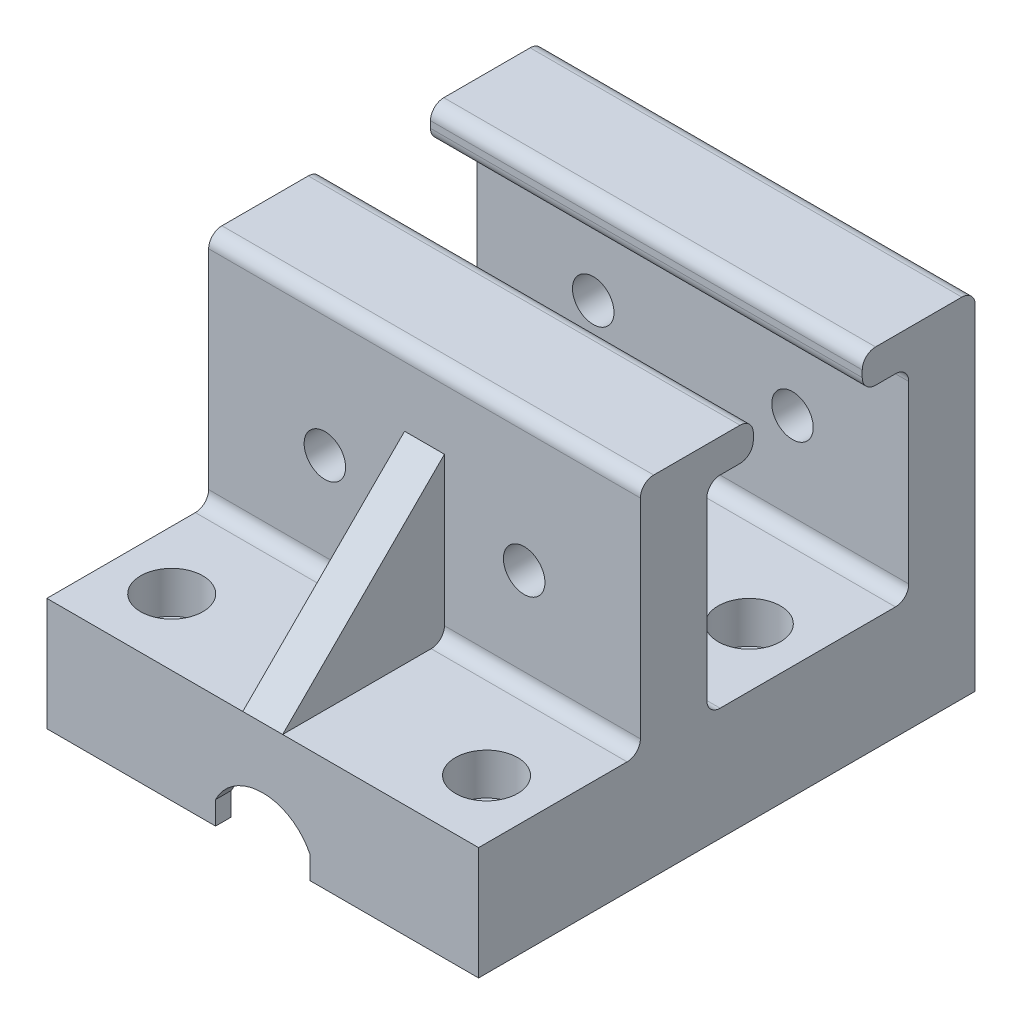
SolidWorks part; units mm, degrees
ref_plane "Front Plane" through (0, 0, 0) normal (0, 0, 1) x (1, 0, 0)
ref_plane "Top Plane" through (0, 0, 0) normal (0, 1, 0) x (1, 0, 0)
ref_plane "Right Plane" through (0, 0, 0) normal (1, 0, 0) x (0, 0, -1)
sketch "Sketch1" plane through (0, 0, 0) normal (0, 0, 1) x (1, 0, 0)
  line L0 (0, 0) -> (0, 28.1718) construction
  line L1 (15.875, 0) -> (41.275, 0)
  line L2 (41.275, 0) -> (41.275, 21.59)
  line L3 (41.275, 21.59) -> (-41.275, 21.59)
  line L4 (-41.275, 0) -> (-41.275, 21.59)
  line L5 (-15.875, 0) -> (-41.275, 0)
  arc A0 (15.875, 0) -> (-15.875, 0) centre (0, 0) ccw
  point P9 (0, 21.59)
  dimension "D1" = 31.75
  dimension "D2" = 25.4
  dimension "D3" = 21.59
extrude "Boss-Extrude1" add sketch "Sketch1" along normal blind 94.9452
sketch "Sketch2" plane through (0, 0, 0) normal (0, 0, -1) x (-1, 0, 0)
  circle A0 centre (0, 0) radius 18.923
  dimension "D1" = 37.846
extrude "Cut-Extrude1" cut sketch "Sketch2" against normal blind 56.9976
sketch "Sketch3" plane through (0, 0, 94.9452) normal (0, 0, 1) x (1, 0, 0)
  line L0 (-9.017, 4.3994) -> (-9.017, 0)
  line L1 (9.017, 4.3994) -> (9.017, 0)
  line L2 (-15.875, 0) -> (-9.017, 0)
  line L3 (15.875, 0) -> (9.017, 0)
  arc A0 (15.875, 0) -> (-15.875, 0) centre (0, 0) ccw
  arc A1 (9.017, 4.3994) -> (-9.017, 4.3994) centre (0, 0) ccw
  arc A2 (15.875, 0) -> (-15.875, 0) centre (0, 0) ccw construction
  dimension "D1" = 20.066
  dimension "D2" = 18.034
extrude "Boss-Extrude2" add sketch "Sketch3" against normal blind 2.9972
ref_plane "Plane1" through (0, 0, 0) normal (1, 0, 0) x (0, 0, -1)
sketch "Sketch6" plane through (0, 0, 0) normal (1, 0, 0) x (0, 0, -1)
  line L0 (-32.004, 21.59) -> (-32.004, 62.0795) construction
  line L1 (-94.9452, 21.59) -> (0, 21.59) construction
  line L2 (0, 21.59) -> (0, 66.548)
  line L3 (0, 66.548) -> (-21.59, 66.548)
  line L4 (-21.59, 66.548) -> (-21.59, 60.198)
  line L5 (-21.59, 60.198) -> (-12.7, 60.198)
  line L6 (-12.7, 60.198) -> (-12.7, 21.59)
  line L7 (-12.7, 21.59) -> (0, 21.59)
  line L8 (-51.308, 21.59) -> (-64.008, 21.59)
  line L9 (-51.308, 60.198) -> (-51.308, 21.59)
  line L10 (-42.418, 60.198) -> (-51.308, 60.198)
  line L11 (-42.418, 66.548) -> (-42.418, 60.198)
  line L12 (-64.008, 66.548) -> (-42.418, 66.548)
  line L13 (-64.008, 21.59) -> (-64.008, 66.548)
  line L14 (0, 0) -> (0, 21.59) construction
  dimension "D1" = 38.608
  dimension "D2" = 12.7
  dimension "D3" = 6.35
  dimension "D4" = 8.89
  dimension "D5" = 38.608
extrude "Boss-Extrude3" add sketch "Sketch6" along normal up to surface and the other way up to surface up to face at (41.275, 10.795, 47.4726) other way up to face at (-41.275, 10.795, 47.4726)
hole_wizard "Hole2" positions "Sketch7" profile "Sketch9" legacy end condition through all
sketch "Sketch7" plane through (0, 21.59, 0) normal (0, 1, 0) x (1, 0, 0)
  line L0 (41.275, -32.004) -> (-41.275, -32.004) construction
  line L1 (41.275, -51.308) -> (41.275, -12.7) construction
  line L2 (-41.275, -51.308) -> (-41.275, -12.7) construction
  line L4 (-30.099, -94.9452) -> (-30.099, -32.004) construction
  line L5 (41.275, -94.9452) -> (-41.275, -94.9452) construction
  line L8 (-41.275, -94.9452) -> (-41.275, 0) construction
  line L9 (-18.923, 0) -> (-18.923, -56.9976) construction
  point P0 (-30.099, -32.004)
  point P2 (-30.099, -82.2452)
  dimension "D1" = 12.7
sketch "Sketch9" plane through (-30.099, 21.59, 32.004) normal (1, 0, 0) x (0, 0, 1)
  line L0 (0, 0) -> (0, 21.59)
  line L1 (0, 21.59) -> (3.9688, 21.59)
  line L2 (3.9688, 21.59) -> (3.9688, 7.9375)
  line L3 (3.9688, 7.9375) -> (5.9531, 7.9375)
  line L4 (5.9531, 7.9375) -> (5.9531, 0)
  line L5 (5.9531, 0) -> (0, 0)
  line L6 (0, 110) -> (0, -10) construction
  dimension "Diameter" = 7.9375
  dimension "Depth" = 21.59
  dimension "C-Bore Diameter" = 11.9062
  dimension "C-Bore Depth" = 7.9375
mirror "Mirror2" about plane through (0, 0, 0) normal (1, 0, 0) of "Hole2"
sketch "Sketch10" plane through (0, 0, 0) normal (0, 0, 1) x (1, 0, 0)
  line L0 (-41.275, 40.894) -> (41.275, 40.894) construction
  line L1 (-41.275, 21.59) -> (-41.275, 66.548) construction
  line L2 (41.275, 21.59) -> (41.275, 66.548) construction
  line L3 (41.275, 21.59) -> (-41.275, 21.59) construction
  line L4 (41.275, 60.198) -> (-41.275, 60.198) construction
  line L5 (0, 66.548) -> (0, 40.894) construction
  line L6 (41.275, 66.548) -> (-41.275, 66.548) construction
  circle A0 centre (-19.05, 40.894) radius 3.9688
  circle A1 centre (19.05, 40.894) radius 3.9688
  dimension "D1" = 38.1
  dimension "D2" = 7.9375
extrude "Cut-Extrude3" cut sketch "Sketch10" against normal through all and the other way through all
sketch "Sketch11" plane through (0, 0, 0) normal (1, 0, 0) x (0, 0, -1)
  line L0 (-94.9452, 21.59) -> (-64.008, 52.5272)
  line L1 (-64.008, 21.59) -> (-64.008, 66.548) construction
  line L2 (-94.9452, 21.59) -> (-64.008, 21.59) construction
  dimension "D1" = 45
rib "Rib1" sketch "Sketch11" sketch "Sketch11" thickness 7.62 extrusion direction parallel to sketch draft on no parameters "D1"=7.62
fillet "Fillet1" radius 2.54 12 edges at (0, 60.198, 42.418) (0, 66.548, 42.418) (0, 66.548, 21.59) (0, 60.198, 21.59) (0, 60.198, 12.7) (0, 60.198, 51.308) (22.5425, 21.59, 64.008) (-22.5425, 21.59, 64.008) (0, 21.59, 51.308) (0, 21.59, 12.7) (0, 66.548, 0) (0, 66.548, 64.008)
